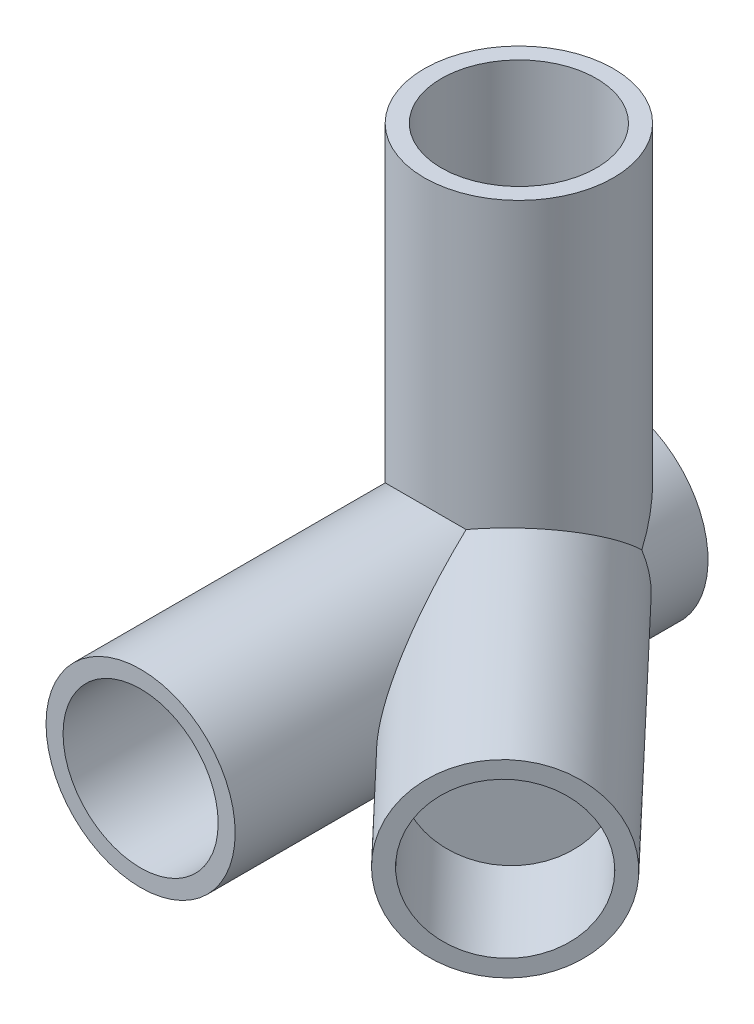
SolidWorks part; units mm, degrees
ref_plane "前视基准面" through (0, 0, 0) normal (0, 0, 1) x (1, 0, 0)
ref_plane "上视基准面" through (0, 0, 0) normal (0, 1, 0) x (1, 0, 0)
ref_plane "右视基准面" through (0, 0, 0) normal (1, 0, 0) x (0, 0, -1)
other "Configuration Table"
sketch "草图1" plane through (0, 0, 0) normal (0, 0, 1) x (1, 0, 0)
  circle A0 centre (0, 0) radius 4.1
  circle A1 centre (0, 0) radius 5
  dimension "D1" = 8.2
  dimension "D2" = 10
extrude "凸台-拉伸1" add sketch "草图1" along normal blind 25
sketch "草图2" plane through (0, 0, 0) normal (0, 1, 0) x (1, 0, 0)
  circle A0 centre (0, -5) radius 5
  circle A1 centre (0, -5) radius 4.1
  dimension "D1" = 8.2
extrude "凸台-拉伸2" add sketch "草图2" along normal blind 20
sketch "草图3" plane through (0, 0, 0) normal (0, 1, 0) x (1, 0, 0)
  line L0 (0, 0) -> (0, -28.9641) construction
  line L1 (0, -5) -> (13.7747, -19.5003)
  line L2 (0, -5) -> (3.6251, -1.5563)
  line L3 (3.6251, -1.5563) -> (17.3998, -16.0566)
  line L4 (17.3998, -16.0566) -> (13.7747, -19.5003)
  circle A2 centre (0, -5) radius 5 construction
  point P13 (17.6777, -15.6066)
  point P14 (13.6818, -19.4025)
  dimension "D1" = 43.53
  dimension "D2" = 20
revolve "旋转2" add sketch "草图3" angle 360 about L1
sketch "草图4" plane through (16.2714, 0, 17.1285) normal (0.6887, 0, 0.725) x (0.725, 0, -0.6887)
  circle A0 centre (-3.4437, 0) radius 4.1
  dimension "D1" = 8.2
extrude "切除-拉伸1" cut sketch "草图4" against normal blind 15
sketch "草图5" plane through (0, 0, 0) normal (0, 0, -1) x (-1, 0, 0)
  circle A0 centre (0, 0) radius 4.5907
extrude "凸台-拉伸3" add sketch "草图5" against normal blind 19
ref_plane "基准面1" through (0, 6, 0) normal (0, 1, 0) x (1, 0, 0)
sketch "草图6" plane through (0, 6, 0) normal (0, 1, 0) x (1, 0, 0)
  circle A0 centre (0, -5) radius 5
extrude "凸台-拉伸4" add sketch "草图6" along normal blind 2
ref_plane "基准面2" through (11.4503, 0, 12.0534) normal (0.6887, 0, 0.725) x (0.725, 0, -0.6887)
sketch "草图10" plane through (11.4503, 0, 12.0534) normal (0.6887, 0, 0.725) x (0.725, 0, -0.6887)
  circle A0 centre (-3.4437, 0) radius 5
extrude "凸台-拉伸5" add sketch "草图10" along normal blind 1
